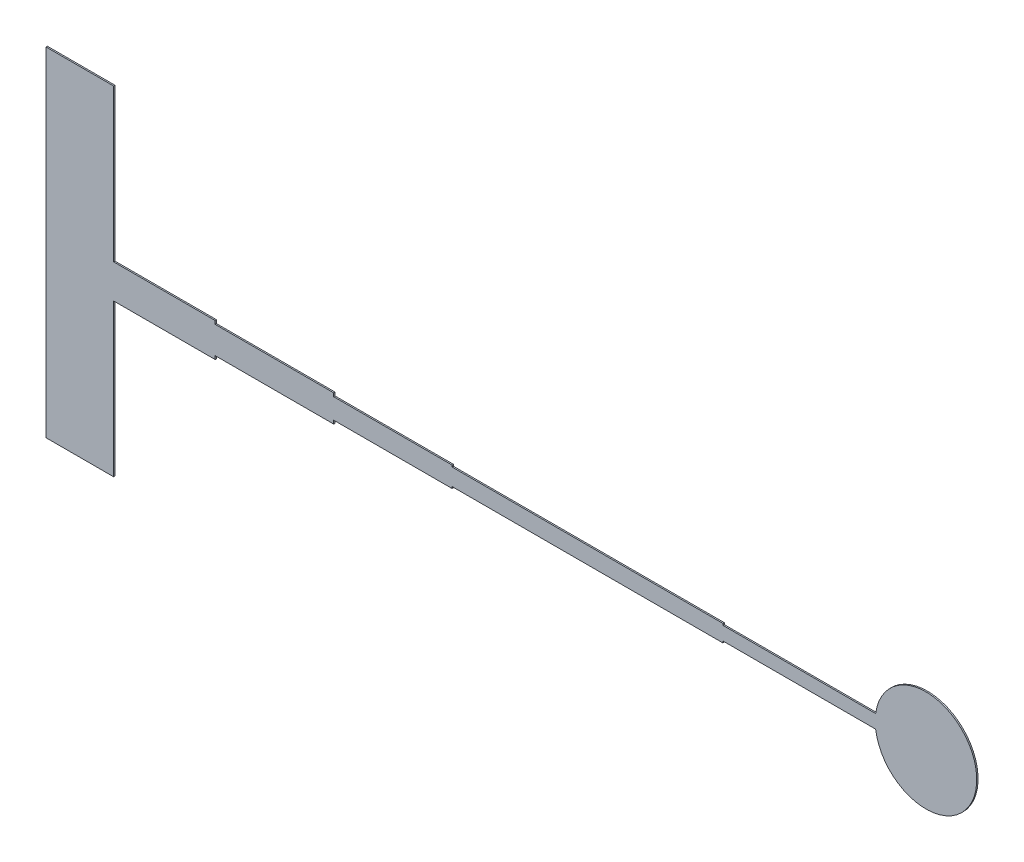
SolidWorks part; units mm, degrees
ref_plane "Front Plane" through (0, 0, 0) normal (0, 0, 1) x (1, 0, 0)
ref_plane "Top Plane" through (0, 0, 0) normal (0, 1, 0) x (1, 0, 0)
ref_plane "Right Plane" through (0, 0, 0) normal (1, 0, 0) x (0, 0, -1)
sketch "Sketch1" plane through (0, 0, 0) normal (0, 0, 1) x (1, 0, 0)
  line L0 (1000, 250) -> (5000, 250)
  line L1 (-1000, 2500) -> (1000, 2500)
  line L2 (-1000, 2500) -> (-1000, -2500)
  line L3 (-1000, -2500) -> (1000, -2500)
  line L4 (1000, 2500) -> (1000, 250)
  line L5 (-1000, 2500) -> (1000, -2500) construction
  line L6 (-1000, -2500) -> (1000, 2500) construction
  line L9 (1000, -250) -> (5000, -250)
  line L10 (5000, 250) -> (5000, 125)
  line L11 (-3000, 250) -> (5000, -250) construction
  line L12 (-3000, -250) -> (5000, 250) construction
  line L13 (5000, 125) -> (9000, 125)
  line L15 (5000, -125) -> (9000, -125)
  line L16 (9000, 125) -> (9000, 100)
  line L17 (1000, 125) -> (9000, -125) construction
  line L18 (1000, -125) -> (9000, 125) construction
  line L19 (9000, 100) -> (11256.6966, 100)
  line L21 (9000, -100) -> (11256.6966, -100)
  line L23 (6000, 100) -> (12000, -100) construction
  line L24 (6000, -100) -> (12000, 100) construction
  line L25 (1000, -250) -> (1000, -2500)
  line L26 (5000, -125) -> (5000, -250)
  line L27 (9000, -100) -> (9000, -125)
  arc A0 (11256.6966, -100) -> (11256.6966, 100) centre (12000, 0) ccw
  point P0 (0, 0)
  point P6 (1000, 0)
  point P11 (5000, 0)
  point P16 (9000, 0)
  dimension "D9" = 1500
  dimension "D1" = 2000
  dimension "D2" = 5000
  dimension "D3" = 500
  dimension "D4" = 4000
  dimension "D5" = 250
  dimension "D6" = 4000
  dimension "D7" = 200
extrude "Boss-Extrude1" add sketch "Sketch1" against normal blind 20
sketch "Sketch2" plane through (0, 0, 0) normal (0, 0, 1) x (1, 0, 0)
  line L0 (0, -11) -> (0, 11) construction
  line L1 (1000, 2500) -> (0, 2500)
  line L2 (1000, 2500) -> (1000, 250)
  line L3 (1000, 250) -> (0, 250)
  line L4 (0, 2500) -> (0, 250)
  line L5 (1000, -2500) -> (0, -2500)
  line L6 (1000, -2500) -> (1000, -250)
  line L7 (1000, -250) -> (0, -250)
  line L8 (0, -2500) -> (0, -250)
  dimension "D1" = 1000
  dimension "D2" = 2250
extrude "Cut-Extrude1" cut sketch "Sketch2" against normal through all
sketch "Sketch3" plane through (0, 0, 0) normal (0, 0, 1) x (1, 0, 0)
  line L0 (0, 0) -> (1098.3807, 0) construction
  line L1 (11, 0) -> (-11, 0) construction
  line L2 (5000, 250) -> (0, 250) construction
  line L3 (1500, 250) -> (3250, 250)
  line L4 (1500, 250) -> (1500, 200)
  line L5 (1500, 200) -> (3250, 200)
  line L7 (0, -250) -> (5000, -250) construction
  line L8 (1500, -250) -> (3250, -250)
  line L9 (1500, -250) -> (1500, -200)
  line L10 (1500, -200) -> (3250, -200)
  line L12 (0, -11) -> (0, 11) construction
  line L13 (3250, 200) -> (3250, 150)
  line L14 (3250, 250) -> (5000, 250)
  line L16 (3250, 150) -> (5000, 150)
  line L17 (5000, 250) -> (5000, 150)
  line L18 (3250, -250) -> (5000, -250)
  line L19 (3250, -200) -> (3250, -150)
  line L20 (3250, -150) -> (5000, -150)
  line L21 (5000, -250) -> (5000, -150)
  point P17 (1500, 225)
  dimension "D1" = 1098.3807
  dimension "D2" = 1750
  dimension "D3" = 50
  dimension "D4" = 1750
  dimension "D5" = 50
  dimension "D6" = 1500
  dimension "D7" = 1500
  dimension "D8" = 100
  dimension "D9" = 100
  dimension "D10" = 1750
  dimension "D11" = 1750
extrude "Cut-Extrude4" cut sketch "Sketch3" against normal through all contours L8 L18 L21 L20 L19 L10 L9
mirror "Mirror1" about plane through (0, 0, 0) normal (0, 1, 0) of "Cut-Extrude4"
